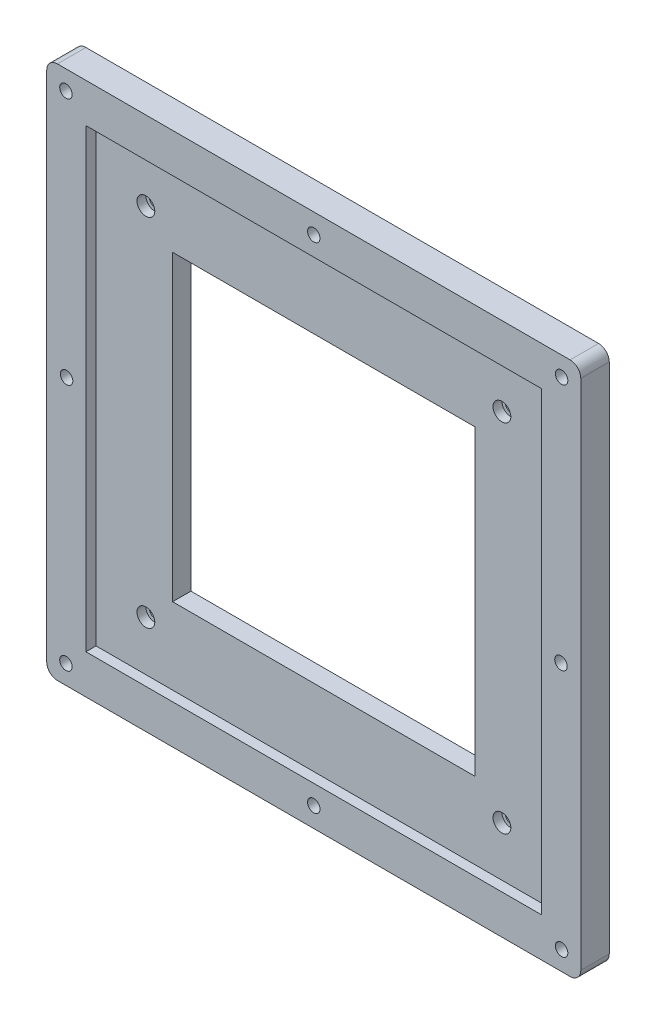
SolidWorks part; units mm, degrees
ref_plane "Спереди" through (0, 0, 0) normal (0, 0, 1) x (1, 0, 0)
ref_plane "Сверху" through (0, 0, 0) normal (0, 1, 0) x (1, 0, 0)
ref_plane "Справа" through (0, 0, 0) normal (1, 0, 0) x (0, 0, -1)
sketch "Sketch1" plane through (0, 0, 0) normal (0, 0, 1) x (1, 0, 0)
  line L1 (-63.5, 63.5) -> (63.5, 63.5) construction
  line L2 (-63.5, 63.5) -> (-63.5, -63.5) construction
  line L3 (-63.5, -63.5) -> (63.5, -63.5) construction
  line L4 (63.5, 63.5) -> (63.5, -63.5) construction
  line L5 (-63.5, 63.5) -> (63.5, -63.5) construction
  line L6 (-63.5, -63.5) -> (63.5, 63.5) construction
  line L7 (-75, 75) -> (75, 75)
  line L8 (-75, 75) -> (-75, -75)
  line L9 (-75, -75) -> (75, -75)
  line L10 (75, 75) -> (75, -75)
  line L11 (-75, 75) -> (75, -75) construction
  line L12 (-75, -75) -> (75, 75) construction
  line L17 (-42.5, 42.5) -> (42.5, 42.5)
  line L18 (-42.5, 42.5) -> (-42.5, -42.5)
  line L19 (-42.5, -42.5) -> (42.5, -42.5)
  line L20 (42.5, 42.5) -> (42.5, -42.5)
  line L21 (-42.5, 42.5) -> (42.5, -42.5) construction
  line L22 (-42.5, -42.5) -> (42.5, 42.5) construction
  line L23 (-50, 50) -> (50, 50) construction
  line L24 (-50, 50) -> (-50, -50) construction
  line L25 (-50, -50) -> (50, -50) construction
  line L26 (50, 50) -> (50, -50) construction
  line L27 (-50, 50) -> (50, -50) construction
  line L28 (-50, -50) -> (50, 50) construction
  circle A0 centre (-50, 50) radius 1.5
  circle A1 centre (50, 50) radius 1.5
  circle A2 centre (50, -50) radius 1.5
  circle A3 centre (-50, -50) radius 1.5
  point P0 (0, 0)
  point P6 (0, 0)
  point P11 (0, 0)
  point P12 (0, 0)
  point P17 (0, 0)
  point P32 (0, 0)
  dimension "D1" = 127
  dimension "D2" = 150
  dimension "D3" = 85
  dimension "D4" = 100
  dimension "D5" = 4
extrude "Boss-Extrude1" add sketch "Sketch1" along normal blind 8
sketch "Sketch3" plane through (0, 0, 8) normal (0, 0, 1) x (1, 0, 0)
  line L1 (-64, 64) -> (64, 64)
  line L2 (-64, 64) -> (-64, -64)
  line L3 (-64, -64) -> (64, -64)
  line L4 (64, 64) -> (64, -64)
  line L5 (-64, 64) -> (64, -64) construction
  line L6 (-64, -64) -> (64, 64) construction
  point P0 (0, 0)
  dimension "D1" = 128
extrude "Cut-Extrude2" cut sketch "Sketch3" against normal blind 2.85
fillet "Fillet1" radius 3 4 edges at (-75, -75, 4) (75, -75, 4) (75, 75, 4) (-75, 75, 4)
sketch "Sketch4" plane through (0, 0, 5.15) normal (0, 0, -1) x (-1, 0, 0)
  circle A0 centre (-50, 50) radius 2.5
  circle A1 centre (50, 50) radius 2.5
  circle A2 centre (50, -50) radius 2.5
  circle A3 centre (-50, -50) radius 2.5
  point P3 (0, 0)
  point P12 (0, 0)
  dimension "D1" = 4
extrude "Cut-Extrude3" cut sketch "Sketch4" along normal blind 2.5
sketch "Sketch5" plane through (0, 0, 8) normal (0, 0, 1) x (1, 0, 0)
  line L0 (0, 0) -> (0, 69.4313) construction
  line L1 (0, 0) -> (-69.6102, 69.6102) construction
  circle A0 centre (0, 69.4313) radius 1.75
  circle A1 centre (-69.6102, 69.6102) radius 1.75
  circle A2 centre (69.4313, 0) radius 1.75
  circle A3 centre (69.6102, 69.6102) radius 1.75
  circle A4 centre (0, -69.4313) radius 1.75
  circle A5 centre (69.6102, -69.6102) radius 1.75
  circle A6 centre (-69.4313, 0) radius 1.75
  circle A7 centre (-69.6102, -69.6102) radius 1.75
  point P23 (0, 0)
  dimension "D1" = 4
extrude "Cut-Extrude4" cut sketch "Sketch5" against normal blind 23
